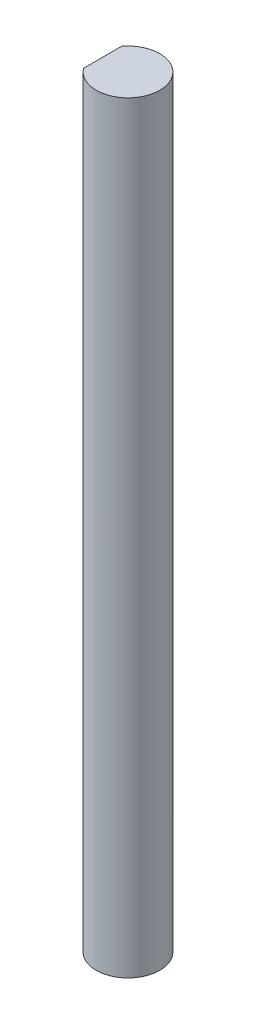
SolidWorks part; units mm, degrees
material "AISI 304"
ref_plane "Plano frontal" through (0, 0, 0) normal (0, 0, 1) x (1, 0, 0)
ref_plane "Plano superior" through (0, 0, 0) normal (0, 1, 0) x (1, 0, 0)
ref_plane "Plano direito" through (0, 0, 0) normal (1, 0, 0) x (0, 0, -1)
sketch "Esboço1" plane through (0, 0, 0) normal (0, 1, 0) x (1, 0, 0)
  circle A0 centre (0, 0) radius 2.5
  dimension "D1" = 5
extrude "Ressalto-extrusão1" add sketch "Esboço1" along normal mid plane 60
sketch "Esboço2" plane through (0, 30, 0) normal (0, 1, 0) x (1, 0, 0)
  line L0 (2.5, 0) -> (-2, 0) construction
  line L1 (-2, -1.5) -> (-2, 1.5)
  circle A0 centre (0, 0) radius 2.5 construction
  arc A1 (-2, 1.5) -> (-2, -1.5) centre (0, 0) ccw
  point P9 (-2, 0)
  dimension "D1" = 4.5
extrude "Corte-extrusão1" cut sketch "Esboço2" against normal blind 15
